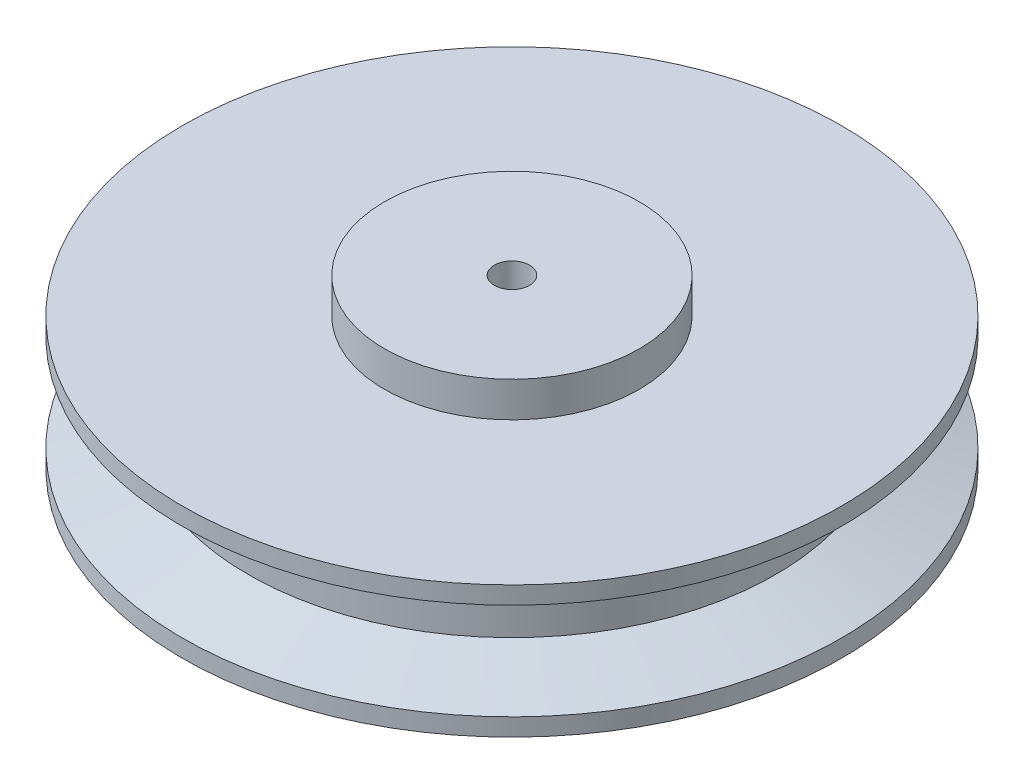
SolidWorks part; units mm, degrees
material "1060 Alloy"
ref_plane "Front Plane" through (0, 0, 0) normal (0, 0, 1) x (1, 0, 0)
ref_plane "Top Plane" through (0, 0, 0) normal (0, 1, 0) x (1, 0, 0)
ref_plane "Right Plane" through (0, 0, 0) normal (1, 0, 0) x (0, 0, -1)
sketch "Sketch1" plane through (0, 0, 0) normal (0, 0, 1) x (1, 0, 0)
  line L0 (0, 0) -> (0, -40) construction
  line L1 (4, 0) -> (4, -29.6158)
  line L7 (75, 0.3842) -> (75, -3.6158)
  line L8 (75, -3.6158) -> (60, -8.6158)
  line L9 (60, -8.6158) -> (60, -20.6158)
  line L11 (60, -20.6158) -> (75, -25.6158)
  line L12 (75, -25.6158) -> (75, -29.6158)
  line L18 (75, -29.6158) -> (4, -29.6158)
  line L19 (4, 0) -> (4, 8.3842)
  line L20 (4, 8.3842) -> (29, 8.3842)
  line L21 (29, 8.3842) -> (29, 0.3842)
  line L22 (29, 0.3842) -> (75, 0.3842)
  dimension "D1" = 4
  dimension "D2" = 75
  dimension "D3" = 4
  dimension "D4" = 4
  dimension "D5" = 0
  dimension "D6" = 15
  dimension "D7" = 12
  dimension "D8" = 5
  dimension "D9" = 5
  dimension "D10" = 25
  dimension "D11" = 8
revolve "Revolve1" add sketch "Sketch1" angle 360 about L0
